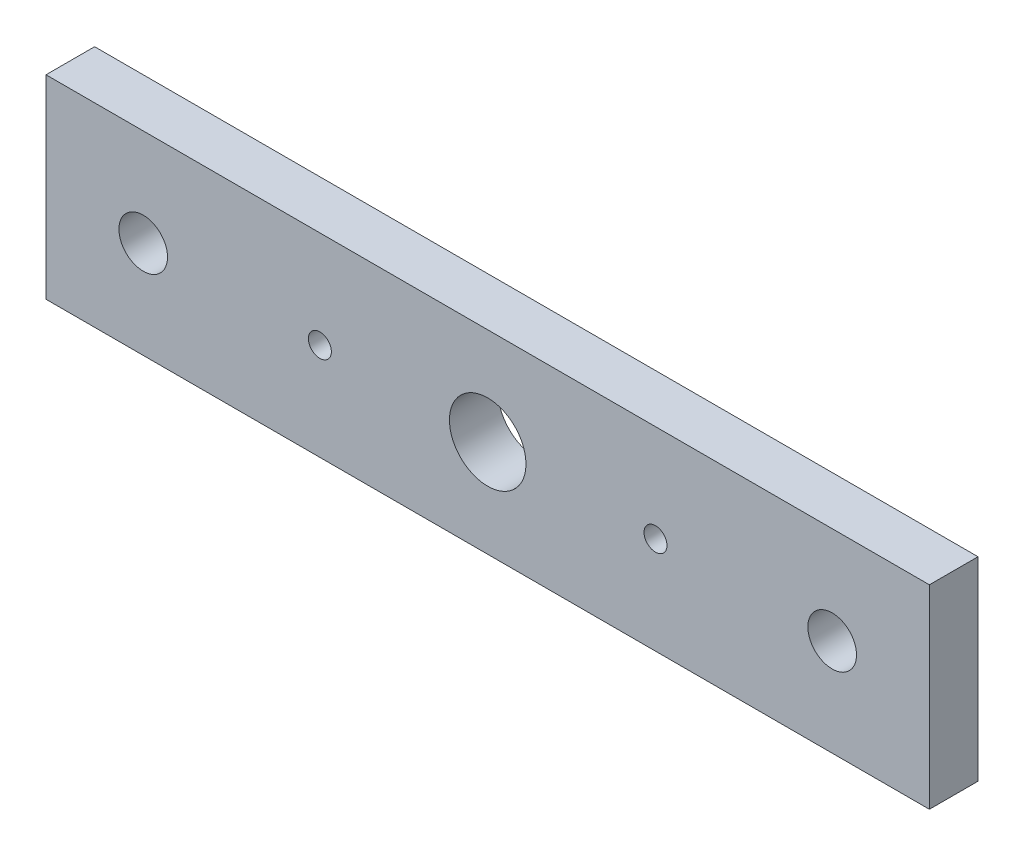
SolidWorks part; units mm, degrees
ref_plane "Front Plane" through (0, 0, 0) normal (0, 0, 1) x (1, 0, 0)
ref_plane "Top Plane" through (0, 0, 0) normal (0, 1, 0) x (1, 0, 0)
ref_plane "Right Plane" through (0, 0, 0) normal (1, 0, 0) x (0, 0, -1)
sketch "Sketch1" plane through (0, 0, 0) normal (1, 0, 0) x (0, 0, -1)
  line L1 (0, 0) -> (6.35, 0)
  line L2 (0, 0) -> (0, 25.4)
  line L3 (0, 25.4) -> (6.35, 25.4)
  line L4 (6.35, 0) -> (6.35, 25.4)
  dimension "D1" = 25.4
  dimension "D2" = 6.35
extrude "Boss-Extrude1" add sketch "Sketch1" along normal blind 115.4
sketch "Sketch2" plane through (0, 0, 0) normal (0, 0, 1) x (1, 0, 0)
  line L0 (0, 12.7) -> (12.7, 12.7) construction
  line L1 (0, 25.4) -> (0, 0) construction
  line L2 (12.7, 12.7) -> (35.7797, 12.7) construction
  line L3 (35.7797, 12.7) -> (57.7, 12.7) construction
  line L4 (57.7, 12.7) -> (79.6203, 12.7) construction
  line L5 (79.6203, 12.7) -> (102.7, 12.7) construction
  line L6 (102.7, 12.7) -> (115.4, 12.7) construction
  line L7 (115.4, 25.4) -> (115.4, 0) construction
  circle A0 centre (57.7, 12.7) radius 5
  circle A1 centre (35.7797, 12.7) radius 1.5
  circle A2 centre (12.7, 12.7) radius 3.175
  circle A3 centre (79.6203, 12.7) radius 1.5
  circle A4 centre (102.7, 12.7) radius 3.175
  dimension "D2" = 6.35
  dimension "D3" = 3
  dimension "D5" = 10
  dimension "D1" = 12.7
  dimension "D4" = 43.8406
  dimension "D6" = 90
extrude "Cut-Extrude1" cut sketch "Sketch2" against normal through all
